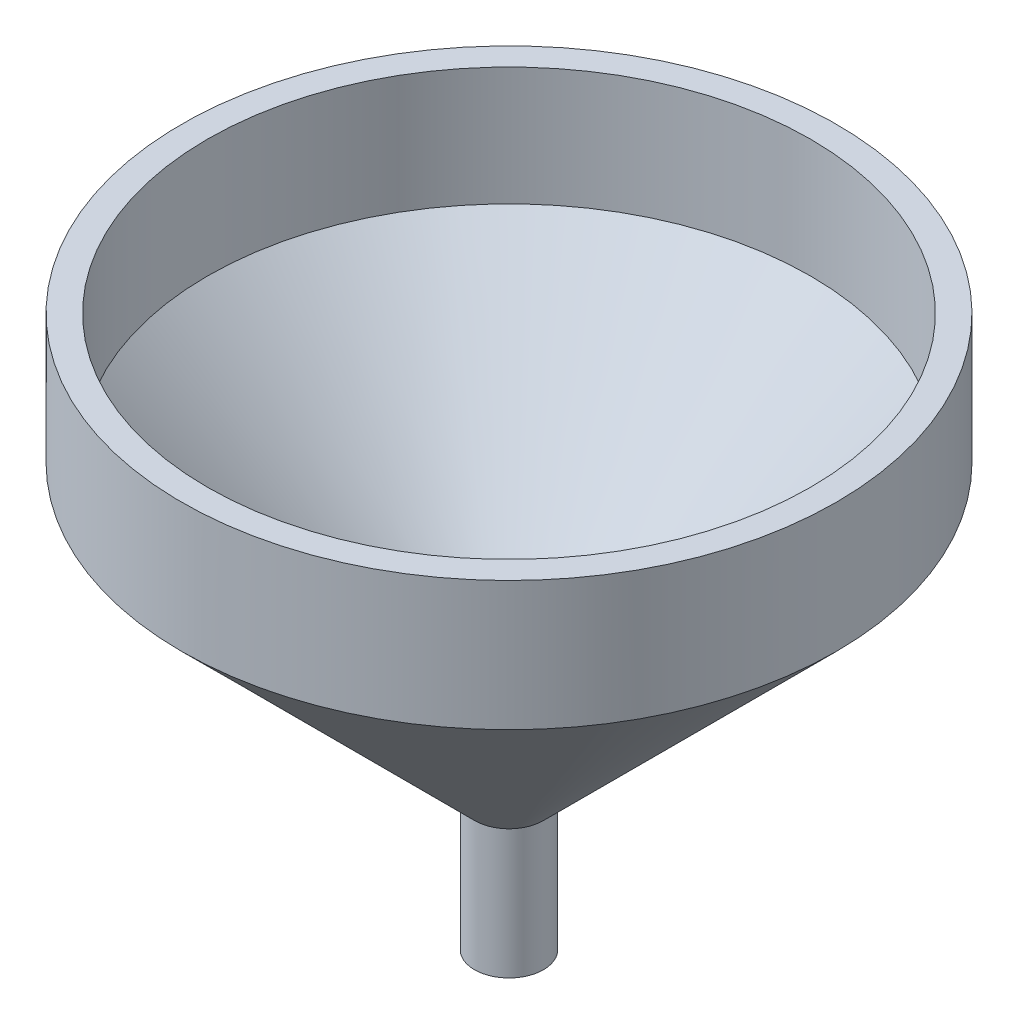
SolidWorks part; units mm, degrees
ref_plane "Front Plane" through (0, 0, 0) normal (0, 0, 1) x (1, 0, 0)
ref_plane "Top Plane" through (0, 0, 0) normal (0, 1, 0) x (1, 0, 0)
ref_plane "Right Plane" through (0, 0, 0) normal (1, 0, 0) x (0, 0, -1)
sketch "basis" plane through (0, 0, 0) normal (0, 0, 1) x (1, 0, 0)
  line L1 (-2, 0) -> (-2, 15)
  line L2 (-2, 15) -> (-36, 49)
  line L3 (-36, 49) -> (-36, 64)
  line L4 (-36, 64) -> (-33, 64)
  line L6 (-33, 64) -> (-33, 50.2426)
  line L7 (-33, 50.2426) -> (0, 17.2426)
  line L8 (0, 17.2426) -> (0, 0)
  line L9 (0, 0) -> (-2, 0)
  line L10 (0, 0) -> (2, 0) construction
  line L11 (2, 0) -> (2, 64) construction
  line L12 (2, 64) -> (-33, 64) construction
  line L13 (0, 17.2426) -> (2, 17.2426) construction
  dimension "D1" = 15
  dimension "D2" = 15
  dimension "D3" = 3
  dimension "D4" = 2
  dimension "D5" = 3
  dimension "D6" = 2
  dimension "D7" = 35
  dimension "D8" = 45
revolve "roteren" add sketch "basis" angle 360 about L11
